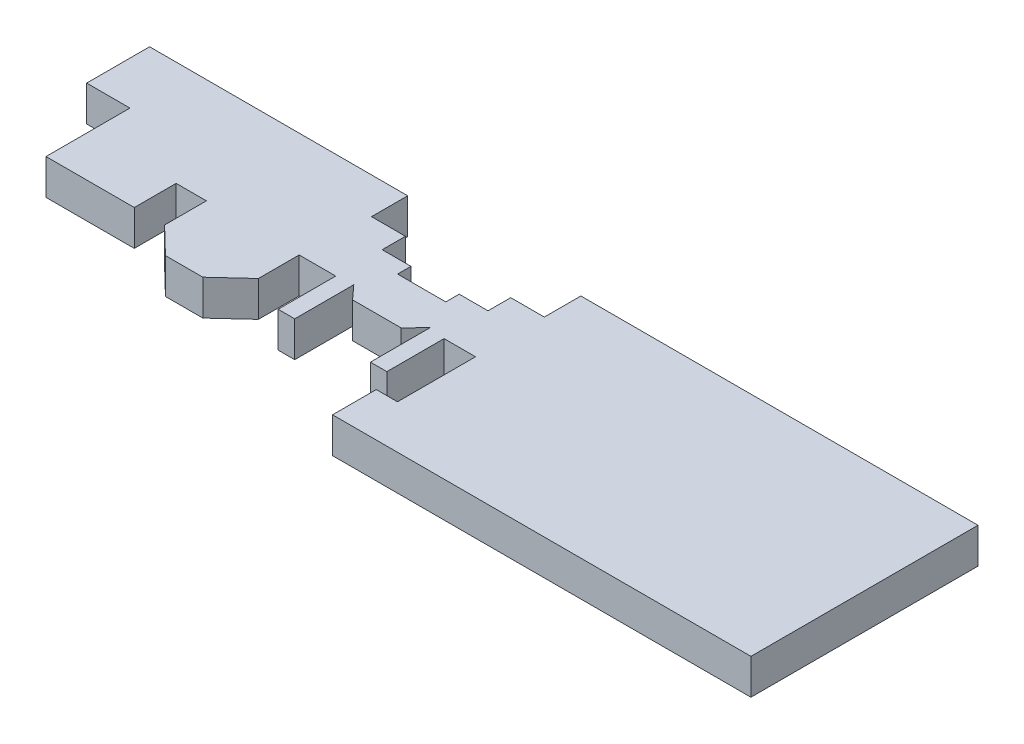
SolidWorks part; units mm, degrees
ref_plane "Front" through (0, 0, 0) normal (0, 0, 1) x (1, 0, 0)
ref_plane "Top" through (0, 0, 0) normal (0, 1, 0) x (1, 0, 0)
ref_plane "Right" through (0, 0, 0) normal (1, 0, 0) x (0, 0, -1)
sketch "Sketch1" plane through (0, 0, 0) normal (0, 1, 0) x (1, 0, 0)
  line L0 (-95852.0448, 1004.5028) -> (-93652.0448, 1004.5028) construction
  line L1 (-92722.4429, 3032.5434) -> (-92722.4429, -4248.038)
  line L2 (-92722.4429, -4248.038) -> (-87714.6303, -4248.038)
  line L3 (-87714.6303, -13961.4489) -> (-77497.684, -13961.4489)
  line L4 (-77497.684, -13961.4489) -> (-77497.684, -9120.8318)
  line L5 (-77497.684, -9120.8318) -> (-73993.9992, -9120.8318)
  line L6 (-73993.9992, -9120.8318) -> (-73993.9992, -13961.4489)
  line L7 (-73993.9992, -13961.4489) -> (-70874.3536, -16978.2439)
  line L8 (-70874.3536, -16978.2439) -> (-66551.4365, -16978.2439)
  line L9 (-66551.4365, -16978.2439) -> (-63204.0372, -13893.8222)
  line L10 (-63204.0372, -13893.8222) -> (-63204.0372, -9177.5359)
  line L11 (-63204.0372, -9177.5359) -> (-58974.2106, -9177.5359)
  line L12 (-58974.2106, -9177.5359) -> (-58974.2106, -15834.789)
  line L13 (-58974.2106, -15834.789) -> (-57060.4997, -15834.789)
  line L14 (-57060.4997, -15834.789) -> (-57060.4997, -8999.6581)
  line L15 (-57060.4997, -8999.6581) -> (-55614.7024, -10587.319)
  line L16 (-55614.7024, -10587.319) -> (-49997.8266, -10587.319)
  line L17 (-49997.8266, -10587.319) -> (-48338.774, -8876.9988)
  line L18 (-48338.774, -8876.9988) -> (-48338.774, -15794.4358)
  line L19 (-48338.774, -15794.4358) -> (-46437.4412, -15794.4358)
  line L20 (-46437.4412, -15794.4358) -> (-46437.4412, -9177.5359)
  line L21 (-46437.4412, -9177.5359) -> (-42795.907, -9177.5359)
  line L22 (-42795.907, -9177.5359) -> (-42795.907, -18201.9351)
  line L23 (-42795.907, -18201.9351) -> (-45253.4333, -18201.9351)
  line L24 (-45253.4333, -18201.9351) -> (-45253.4333, -23262.6588)
  line L25 (-45253.4333, -23262.6588) -> (3158.9575, -23262.6588)
  line L26 (3158.9575, -23262.6588) -> (3158.9575, 3013.36)
  line L27 (3158.9575, 3013.36) -> (-42795.907, 3013.36)
  line L28 (-42795.907, 3013.36) -> (-42795.907, -1217.3234)
  line L29 (-42795.907, -1217.3234) -> (-44543.9492, -1217.3234)
  line L30 (-44543.9492, -1217.3234) -> (-44543.9492, -1414.4498)
  line L31 (-44543.9492, -1414.4498) -> (-42795.907, -1414.4498)
  line L32 (-42795.907, -1414.4498) -> (-42795.907, -5614.4796)
  line L33 (-42795.907, -5614.4796) -> (-15610.0343, -5614.4796)
  line L34 (-15610.0343, -5614.4796) -> (-15610.0343, -1822.8901)
  line L35 (-15610.0343, -1822.8901) -> (-2613.5, -1822.8901)
  line L36 (-2613.5, -1822.8901) -> (-2613.5, 969.6477)
  line L37 (-2613.5, 969.6477) -> (-646.0273, 969.6477)
  line L38 (-646.0273, 969.6477) -> (-646.0273, -9455.9367)
  line L39 (-646.0273, -9455.9367) -> (-2613.5, -9455.9367)
  line L40 (-2613.5, -9455.9367) -> (-2613.5, -5114.7195)
  line L41 (-2613.5, -5114.7195) -> (-12313.0283, -5114.7195)
  line L42 (-12313.0283, -5114.7195) -> (-12313.0283, -11916.6398)
  line L43 (-12313.0283, -11916.6398) -> (3158.9575, -11916.6398)
  line L44 (-62020.0141, -5163.6876) -> (-62020.0141, -5388.889)
  line L45 (-62020.0141, -5388.889) -> (-61911.5095, -5388.889)
  line L46 (-61911.5095, -5388.889) -> (-61911.5095, -5437.5424)
  line L47 (-61911.5095, -5437.5424) -> (-61719.1755, -5437.5424)
  line L48 (-61719.1755, -5437.5424) -> (-61719.1755, -5388.889)
  line L49 (-61719.1755, -5388.889) -> (-61612.0786, -5388.889)
  line L50 (-61612.0786, -5388.889) -> (-61612.0786, -5163.6876)
  line L52 (-61970.0141, -5113.6876) -> (-61662.0786, -5113.6876)
  line L54 (-55960.8823, -4121.4792) -> (-55960.8823, -5665.3674)
  line L55 (-55960.8823, -5665.3674) -> (-49725.6524, -5665.3674)
  line L56 (-49725.6524, -5665.3674) -> (-49725.6524, -4121.4792)
  line L57 (-49725.6524, -4121.4792) -> (-46460.002, -4121.4792)
  line L58 (-46460.002, -4121.4792) -> (-46460.002, 2994.9561)
  line L59 (-47960.002, 4494.9561) -> (-57726.5326, 4494.9561)
  line L60 (-55960.8823, -4121.4792) -> (-59226.5326, -4121.4792)
  line L61 (-59226.5326, -4121.4792) -> (-59226.5326, 2994.9561)
  line L62 (3158.9575, -15328.6011) -> (-37892.4286, -15328.6011)
  line L63 (-37892.4286, -15328.6011) -> (-37892.4286, -18201.9351)
  line L64 (-37892.4286, -18201.9351) -> (-35343.2964, -18201.9351)
  line L65 (-35343.2964, -18201.9351) -> (-35343.2964, -20101.0171)
  line L66 (-35343.2964, -20101.0171) -> (-40314.0738, -20101.0171)
  line L67 (-40314.0738, -20101.0171) -> (-40314.0738, -14936.1956)
  line L68 (-40314.0738, -14936.1956) -> (-42544.3056, -14936.1956)
  line L69 (-42544.3056, -14936.1956) -> (-42544.3056, -13384.4604)
  line L70 (-42544.3056, -13384.4604) -> (-40314.0738, -13384.4604)
  line L71 (-40314.0738, -13384.4604) -> (-40314.0738, -8605.2168)
  line L72 (-50136.471, -10373.3274) -> (-48338.774, -8619.2363)
  line L73 (-48338.774, -8619.2363) -> (-40314.0738, -8605.2168)
  line L76 (-50136.471, -10373.3274) -> (-55355.7793, -10373.3274)
  line L77 (-55355.7793, -10373.3274) -> (-57060.4997, -8626.2285)
  line L78 (-57060.4997, -8626.2285) -> (-63481.1822, -8626.2285)
  line L79 (-63481.1822, -8626.2285) -> (-63481.1822, -13591.9685)
  line L80 (-63481.1822, -13591.9685) -> (-66551.4365, -16662.2229)
  line L81 (-66551.4365, -16662.2229) -> (-70681.0433, -16662.2229)
  line L82 (-70681.0433, -16662.2229) -> (-73704.5204, -13701.7349)
  line L83 (-73704.5204, -13701.7349) -> (-73704.5204, -5657.4342)
  line L84 (-73704.5204, -5657.4342) -> (-69334.0401, -5657.4342)
  line L85 (-69334.0401, -5657.4342) -> (-69334.0401, -2723.9748)
  line L86 (-69334.0401, -2723.9748) -> (-77712.6536, -2723.9748)
  line L87 (-77712.6536, -2723.9748) -> (-77712.6536, -3732.5162)
  line L88 (-87714.6303, -4248.038) -> (-87714.6303, -13961.4489)
  line L89 (-92722.4429, 3032.5434) -> (-62854.9695, 3032.5434)
  line L91 (-62893.6785, -5660.1107) -> (-66861.7243, -5660.1107)
  line L92 (-66861.7243, -5660.1107) -> (-66861.7243, -2698.1933)
  line L93 (-66861.7243, -2698.1933) -> (-65946.0214, -2698.1933)
  line L94 (-65946.0214, -2698.1933) -> (-65946.0214, -1043.5021)
  line L95 (-65946.0214, -1043.5021) -> (-87423.7151, -1043.5021)
  line L96 (-87423.7151, -1043.5021) -> (-87423.7151, -8904.221)
  line L97 (-87423.7151, -8904.221) -> (-84329.7257, -8904.221)
  line L98 (-84329.7257, -8904.221) -> (-84329.7257, -10733.514)
  line L99 (-84329.7257, -10733.514) -> (-82681.1037, -10733.514)
  line L100 (-82681.1037, -10733.514) -> (-82681.1037, -2716.2423)
  line L101 (-82681.1037, -2716.2423) -> (-79338.6918, -2716.2423)
  line L102 (-77712.6536, -3732.5162) -> (-79338.6918, -3732.5162)
  line L103 (-79338.6918, -3732.5162) -> (-79338.6918, -2716.2423)
  line L104 (-62854.9695, 3032.5434) -> (-62854.9695, -1153.6152)
  line L105 (-62854.9695, -1153.6152) -> (-61139.275, -1153.6152)
  line L106 (-61139.275, -1153.6152) -> (-61139.275, -1541.516)
  line L107 (-61139.275, -1541.516) -> (-62893.6785, -1541.516)
  line L108 (-62893.6785, -1541.516) -> (-62893.6785, -5660.1107)
  arc A0 (-62020.0141, -5163.6876) -> (-61970.0141, -5113.6876) centre (-61970.0141, -5163.6876) cw
  arc A1 (-61662.0786, -5113.6876) -> (-61612.0786, -5163.6876) centre (-61662.0786, -5163.6876) cw
  arc A2 (-59226.5326, 2994.9561) -> (-57726.5326, 4494.9561) centre (-57726.5326, 2994.9561) cw
  arc A3 (-46460.002, 2994.9561) -> (-47960.002, 4494.9561) centre (-47960.002, 2994.9561) ccw
  dimension "D1" = 50
  dimension "D2" = 50
  dimension "D3" = 1500
  dimension "D4" = 1500
sketch "Sketch5" plane through (0, 0, 0) normal (0, 1, 0) x (1, 0, 0)
  line L0 (-95852.0448, 1004.5028) -> (-93652.0448, 1004.5028) construction
  line L1 (-92722.4429, 3032.5434) -> (-92722.4429, -4248.038)
  line L2 (-92722.4429, -4248.038) -> (-87714.6303, -4248.038)
  line L3 (-87714.6303, -13961.4489) -> (-77497.684, -13961.4489)
  line L4 (-77497.684, -13961.4489) -> (-77497.684, -9120.8318)
  line L5 (-77497.684, -9120.8318) -> (-73993.9992, -9120.8318)
  line L6 (-73993.9992, -9120.8318) -> (-73993.9992, -13961.4489)
  line L7 (-73993.9992, -13961.4489) -> (-70874.3536, -16978.2439)
  line L8 (-70874.3536, -16978.2439) -> (-66551.4365, -16978.2439)
  line L9 (-66551.4365, -16978.2439) -> (-63204.0372, -13893.8222)
  line L10 (-63204.0372, -13893.8222) -> (-63204.0372, -9177.5359)
  line L11 (-63204.0372, -9177.5359) -> (-58974.2106, -9177.5359)
  line L12 (-58974.2106, -9177.5359) -> (-58974.2106, -15834.789)
  line L13 (-58974.2106, -15834.789) -> (-57060.4997, -15834.789)
  line L14 (-57060.4997, -15834.789) -> (-57060.4997, -8999.6581)
  line L15 (-57060.4997, -8999.6581) -> (-55614.7024, -10587.319)
  line L16 (-55614.7024, -10587.319) -> (-49997.8266, -10587.319)
  line L17 (-49997.8266, -10587.319) -> (-48338.774, -8876.9988)
  line L18 (-48338.774, -8876.9988) -> (-48338.774, -15794.4358)
  line L19 (-48338.774, -15794.4358) -> (-46437.4412, -15794.4358)
  line L20 (-46437.4412, -15794.4358) -> (-46437.4412, -9177.5359)
  line L21 (-46437.4412, -9177.5359) -> (-42795.907, -9177.5359)
  line L22 (-42795.907, -9177.5359) -> (-42795.907, -18201.9351)
  line L23 (-42795.907, -18201.9351) -> (-45253.4333, -18201.9351)
  line L24 (-45253.4333, -18201.9351) -> (-45253.4333, -23262.6588)
  line L25 (-45253.4333, -23262.6588) -> (3158.9575, -23262.6588)
  line L26 (3158.9575, -23262.6588) -> (3158.9575, 3013.36)
  line L27 (3158.9575, 3013.36) -> (-42795.907, 3013.36)
  line L28 (-42795.907, 3013.36) -> (-42795.907, -1217.3234)
  line L29 (-42795.907, -1217.3234) -> (-46681.2907, -1217.3234)
  line L30 (-46460.002, -4121.4792) -> (-46460.002, 2994.9561) construction
  line L31 (-46460.002, -1414.4498) -> (-42795.907, -1414.4498)
  line L32 (-42795.907, -1414.4498) -> (-42795.907, -5614.4796)
  line L33 (-42795.907, -5614.4796) -> (-15610.0343, -5614.4796)
  line L34 (-15610.0343, -5614.4796) -> (-15610.0343, -1822.8901)
  line L35 (-15610.0343, -1822.8901) -> (-2613.5, -1822.8901)
  line L36 (-2613.5, -1822.8901) -> (-2613.5, 969.6477)
  line L37 (-2613.5, 969.6477) -> (-646.0273, 969.6477)
  line L38 (-646.0273, 969.6477) -> (-646.0273, -9455.9367)
  line L39 (-646.0273, -9455.9367) -> (-2613.5, -9455.9367)
  line L40 (-2613.5, -9455.9367) -> (-2613.5, -5114.7195)
  line L41 (-2613.5, -5114.7195) -> (-12313.0283, -5114.7195)
  line L42 (-12313.0283, -5114.7195) -> (-12313.0283, -11916.6398)
  line L43 (-12313.0283, -11916.6398) -> (3158.9575, -11916.6398)
  line L54 (-55960.8823, -4121.4792) -> (-55960.8823, -5665.3674)
  line L55 (-55960.8823, -5665.3674) -> (-49725.6524, -5665.3674)
  line L56 (-49725.6524, -5665.3674) -> (-49725.6524, -4121.4792)
  line L57 (-49725.6524, -4121.4792) -> (-46460.002, -4121.4792)
  line L58 (-46460.002, -4121.4792) -> (-46460.002, -1414.4498)
  line L60 (-55960.8823, -4121.4792) -> (-59226.5326, -4121.4792)
  line L61 (-59226.5326, -4121.4792) -> (-59226.5326, -1541.516)
  line L62 (3158.9575, -15328.6011) -> (-37892.4286, -15328.6011)
  line L63 (-37892.4286, -15328.6011) -> (-37892.4286, -18201.9351)
  line L64 (-37892.4286, -18201.9351) -> (-35343.2964, -18201.9351)
  line L65 (-35343.2964, -18201.9351) -> (-35343.2964, -20101.0171)
  line L66 (-35343.2964, -20101.0171) -> (-40314.0738, -20101.0171)
  line L67 (-40314.0738, -20101.0171) -> (-40314.0738, -14936.1956)
  line L68 (-40314.0738, -14936.1956) -> (-42544.3056, -14936.1956)
  line L69 (-42544.3056, -14936.1956) -> (-42544.3056, -13384.4604)
  line L70 (-42544.3056, -13384.4604) -> (-40314.0738, -13384.4604)
  line L71 (-40314.0738, -13384.4604) -> (-40314.0738, -8605.2168)
  line L72 (-50136.471, -10373.3274) -> (-48338.774, -8619.2363)
  line L73 (-48338.774, -8619.2363) -> (-40314.0738, -8605.2168)
  line L76 (-50136.471, -10373.3274) -> (-55355.7793, -10373.3274)
  line L77 (-55355.7793, -10373.3274) -> (-57060.4997, -8626.2285)
  line L78 (-57060.4997, -8626.2285) -> (-63481.1822, -8626.2285)
  line L79 (-63481.1822, -8626.2285) -> (-63481.1822, -13591.9685)
  line L80 (-63481.1822, -13591.9685) -> (-66551.4365, -16662.2229)
  line L81 (-66551.4365, -16662.2229) -> (-70681.0433, -16662.2229)
  line L82 (-70681.0433, -16662.2229) -> (-73704.5204, -13701.7349)
  line L83 (-73704.5204, -13701.7349) -> (-73704.5204, -5657.4342)
  line L84 (-73704.5204, -5657.4342) -> (-69334.0401, -5657.4342)
  line L85 (-69334.0401, -5657.4342) -> (-69334.0401, -2723.9748)
  line L86 (-69334.0401, -2723.9748) -> (-77712.6536, -2723.9748)
  line L87 (-77712.6536, -2723.9748) -> (-77712.6536, -3732.5162)
  line L88 (-87714.6303, -4248.038) -> (-87714.6303, -13961.4489)
  line L89 (-92722.4429, 3032.5434) -> (-62854.9695, 3032.5434)
  line L91 (-62893.6785, -5660.1107) -> (-66861.7243, -5660.1107)
  line L92 (-66861.7243, -5660.1107) -> (-66861.7243, -2698.1933)
  line L93 (-66861.7243, -2698.1933) -> (-65946.0214, -2698.1933)
  line L94 (-65946.0214, -2698.1933) -> (-65946.0214, -1043.5021)
  line L95 (-65946.0214, -1043.5021) -> (-87423.7151, -1043.5021)
  line L96 (-87423.7151, -1043.5021) -> (-87423.7151, -8904.221)
  line L97 (-87423.7151, -8904.221) -> (-84329.7257, -8904.221)
  line L98 (-84329.7257, -8904.221) -> (-84329.7257, -10733.514)
  line L99 (-84329.7257, -10733.514) -> (-82681.1037, -10733.514)
  line L100 (-82681.1037, -10733.514) -> (-82681.1037, -2716.2423)
  line L101 (-82681.1037, -2716.2423) -> (-79338.6918, -2716.2423)
  line L102 (-77712.6536, -3732.5162) -> (-79338.6918, -3732.5162)
  line L103 (-79338.6918, -3732.5162) -> (-79338.6918, -2716.2423)
  line L104 (-62854.9695, 3032.5434) -> (-62854.9695, -1153.6152)
  line L105 (-62854.9695, -1153.6152) -> (-58927.043, -1153.6152)
  line L107 (-59226.5326, -1541.516) -> (-62893.6785, -1541.516)
  line L108 (-62893.6785, -1541.516) -> (-62893.6785, -5660.1107)
  line L110 (-55593.7762, -5398.4292) -> (-50014.5574, -5398.4292)
  line L111 (-46681.2907, -3848.0726) -> (-46681.2907, -1217.3234)
  line L112 (-55593.7762, -3848.0726) -> (-55593.7762, -5398.4292)
  line L113 (-58927.043, -3848.0726) -> (-58927.043, -1153.6152)
  line L114 (-50014.5574, -5398.4292) -> (-50014.5574, -3848.0726)
  line L115 (-50014.5574, -3848.0726) -> (-46681.2907, -3848.0726)
  line L116 (-55593.7762, -3848.0726) -> (-58927.043, -3848.0726)
extrude "Boss-Extrude1" add sketch "Sketch5" along normal blind 4100
ref_plane "Plane1" through (0, 0, -3022.9517) normal (0, 0, -1) x (-1, 0, 0)
sketch "Sketch8" plane through (0, 0, -3022.9517) normal (0, 0, -1) x (-1, 0, 0)
  line L0 (3231.2525, 3102.6563) -> (7231.2525, 3102.6563)
  line L1 (-2028.4059, 3102.6563) -> (1971.5941, 3102.6563)
  line L2 (-2028.4059, 3102.6563) -> (-2028.4059, 1527.9311)
  line L3 (-2028.4059, 1527.9311) -> (1971.5941, 1527.9311)
  line L4 (1971.5941, 3102.6563) -> (1971.5941, 1527.9311)
  line L9 (3231.2525, 1527.9311) -> (7231.2525, 1527.9311)
  line L10 (7231.2525, 3102.6563) -> (7231.2525, 1527.9311)
  line L11 (3231.2525, 3102.6563) -> (3231.2525, 1527.9311)
  line L12 (17815.6364, 3102.6563) -> (17815.6364, 1527.9311)
  line L13 (8555.978, 3102.6563) -> (12555.978, 3102.6563)
  line L14 (13815.6364, 3102.6563) -> (13815.6364, 1527.9311)
  line L15 (13815.6364, 1527.9311) -> (17815.6364, 1527.9311)
  line L16 (13815.6364, 3102.6563) -> (17815.6364, 3102.6563)
  line L17 (8555.978, 3102.6563) -> (8555.978, 1527.9311)
  line L18 (8555.978, 1527.9311) -> (12555.978, 1527.9311)
  line L19 (12555.978, 3102.6563) -> (12555.978, 1527.9311)
  line L20 (25763.8862, 3102.6563) -> (25763.8862, 1527.9311)
  line L21 (21763.8862, 3102.6563) -> (21763.8862, 1527.9311)
  line L22 (21763.8862, 1527.9311) -> (25763.8862, 1527.9311)
  line L23 (41607.9286, 3102.6563) -> (41607.9286, 1527.9311)
  line L24 (27023.5446, 1527.9311) -> (31023.5446, 1527.9311)
  line L25 (21763.8862, 3102.6563) -> (25763.8862, 3102.6563)
  line L26 (37607.9286, 1527.9311) -> (41607.9286, 1527.9311)
  line L27 (32348.2702, 1527.9311) -> (36348.2702, 1527.9311)
  line L28 (27023.5446, 3102.6563) -> (27023.5446, 1527.9311)
  line L29 (37607.9286, 3102.6563) -> (41607.9286, 3102.6563)
  line L30 (31023.5446, 3102.6563) -> (31023.5446, 1527.9311)
  line L31 (32348.2702, 3102.6563) -> (32348.2702, 1527.9311)
  line L32 (36348.2702, 3102.6563) -> (36348.2702, 1527.9311)
  line L33 (37607.9286, 3102.6563) -> (37607.9286, 1527.9311)
  line L34 (27023.5446, 3102.6563) -> (31023.5446, 3102.6563)
  line L35 (32348.2702, 3102.6563) -> (36348.2702, 3102.6563)
  line L36 (70871.2704, 3102.6563) -> (74871.2704, 3102.6563)
  line L37 (81455.6543, 1527.9311) -> (85455.6543, 1527.9311)
  line L38 (90715.3127, 3102.6563) -> (90715.3127, 1527.9311)
  line L39 (85455.6543, 3102.6563) -> (85455.6543, 1527.9311)
  line L40 (70871.2704, 3102.6563) -> (70871.2704, 1527.9311)
  line L41 (76130.9288, 3102.6563) -> (76130.9288, 1527.9311)
  line L42 (86715.3127, 3102.6563) -> (86715.3127, 1527.9311)
  line L43 (80130.9288, 3102.6563) -> (80130.9288, 1527.9311)
  line L44 (86715.3127, 1527.9311) -> (90715.3127, 1527.9311)
  line L45 (86715.3127, 3102.6563) -> (90715.3127, 3102.6563)
  line L46 (76130.9288, 1527.9311) -> (80130.9288, 1527.9311)
  line L47 (76130.9288, 3102.6563) -> (80130.9288, 3102.6563)
  line L48 (70871.2704, 1527.9311) -> (74871.2704, 1527.9311)
  line L49 (81455.6543, 3102.6563) -> (81455.6543, 1527.9311)
  line L50 (74871.2704, 3102.6563) -> (74871.2704, 1527.9311)
  line L51 (81455.6543, 3102.6563) -> (85455.6543, 3102.6563)
  line L52 (65598.8585, 3102.6563) -> (69598.8585, 3102.6563)
  line L53 (69598.8585, 3102.6563) -> (69598.8585, 1527.9311)
  line L54 (65598.8585, 1527.9311) -> (69598.8585, 1527.9311)
  line L55 (65598.8585, 3102.6563) -> (65598.8585, 1527.9311)
sketch "Sketch10" plane through (0, 0, -3022.9517) normal (0, 0, -1) x (-1, 0, 0)
  line L0 (3231.2525, 3102.6563) -> (7231.2525, 3102.6563)
  line L1 (-2028.4059, 3102.6563) -> (1971.5941, 3102.6563)
  line L2 (-2028.4059, 3102.6563) -> (-2028.4059, 1527.9311)
  line L3 (-2028.4059, 1527.9311) -> (1971.5941, 1527.9311)
  line L4 (1971.5941, 3102.6563) -> (1971.5941, 1527.9311)
  line L9 (3231.2525, 1527.9311) -> (7231.2525, 1527.9311)
  line L10 (7231.2525, 3102.6563) -> (7231.2525, 1527.9311)
  line L11 (3231.2525, 3102.6563) -> (3231.2525, 1527.9311)
  line L12 (17815.6364, 3102.6563) -> (17815.6364, 1527.9311)
  line L13 (8555.978, 3102.6563) -> (12555.978, 3102.6563)
  line L14 (13815.6364, 3102.6563) -> (13815.6364, 1527.9311)
  line L15 (13815.6364, 1527.9311) -> (17815.6364, 1527.9311)
  line L16 (13815.6364, 3102.6563) -> (17815.6364, 3102.6563)
  line L17 (8555.978, 3102.6563) -> (8555.978, 1527.9311)
  line L18 (8555.978, 1527.9311) -> (12555.978, 1527.9311)
  line L19 (12555.978, 3102.6563) -> (12555.978, 1527.9311)
  line L20 (25763.8862, 3102.6563) -> (25763.8862, 1527.9311)
  line L21 (21763.8862, 3102.6563) -> (21763.8862, 1527.9311)
  line L22 (21763.8862, 1527.9311) -> (25763.8862, 1527.9311)
  line L23 (41607.9286, 3102.6563) -> (41607.9286, 1527.9311)
  line L24 (27023.5446, 1527.9311) -> (31023.5446, 1527.9311)
  line L25 (21763.8862, 3102.6563) -> (25763.8862, 3102.6563)
  line L26 (37607.9286, 1527.9311) -> (41607.9286, 1527.9311)
  line L27 (32348.2702, 1527.9311) -> (36348.2702, 1527.9311)
  line L28 (27023.5446, 3102.6563) -> (27023.5446, 1527.9311)
  line L29 (37607.9286, 3102.6563) -> (41607.9286, 3102.6563)
  line L30 (31023.5446, 3102.6563) -> (31023.5446, 1527.9311)
  line L31 (32348.2702, 3102.6563) -> (32348.2702, 1527.9311)
  line L32 (36348.2702, 3102.6563) -> (36348.2702, 1527.9311)
  line L33 (37607.9286, 3102.6563) -> (37607.9286, 1527.9311)
  line L34 (27023.5446, 3102.6563) -> (31023.5446, 3102.6563)
  line L35 (32348.2702, 3102.6563) -> (36348.2702, 3102.6563)
  line L36 (70871.2704, 3102.6563) -> (74871.2704, 3102.6563)
  line L37 (81455.6543, 1527.9311) -> (85455.6543, 1527.9311)
  line L38 (90715.3127, 3102.6563) -> (90715.3127, 1527.9311)
  line L39 (85455.6543, 3102.6563) -> (85455.6543, 1527.9311)
  line L40 (70871.2704, 3102.6563) -> (70871.2704, 1527.9311)
  line L41 (76130.9288, 3102.6563) -> (76130.9288, 1527.9311)
  line L42 (86715.3127, 3102.6563) -> (86715.3127, 1527.9311)
  line L43 (80130.9288, 3102.6563) -> (80130.9288, 1527.9311)
  line L44 (86715.3127, 1527.9311) -> (90715.3127, 1527.9311)
  line L45 (86715.3127, 3102.6563) -> (90715.3127, 3102.6563)
  line L46 (76130.9288, 1527.9311) -> (80130.9288, 1527.9311)
  line L47 (76130.9288, 3102.6563) -> (80130.9288, 3102.6563)
  line L48 (70871.2704, 1527.9311) -> (74871.2704, 1527.9311)
  line L49 (81455.6543, 3102.6563) -> (81455.6543, 1527.9311)
  line L50 (74871.2704, 3102.6563) -> (74871.2704, 1527.9311)
  line L51 (81455.6543, 3102.6563) -> (85455.6543, 3102.6563)
  line L52 (65598.8585, 3102.6563) -> (69598.8585, 3102.6563)
  line L53 (69598.8585, 3102.6563) -> (69598.8585, 1527.9311)
  line L54 (65598.8585, 1527.9311) -> (69598.8585, 1527.9311)
  line L55 (65598.8585, 3102.6563) -> (65598.8585, 1527.9311)
extrude "Cut-Extrude2" cut sketch "Sketch8" against normal blind 1000 and the other way blind 360
ref_plane "Plane2" through (0, 4100, 0) normal (0, 1, 0) x (1, 0, 0)
sketch "Sketch11" plane through (0, 4100, 0) normal (0, 1, 0) x (1, 0, 0)
  line L0 (-95852.0448, 1004.5028) -> (-93652.0448, 1004.5028) construction
  line L1 (-92722.4429, 3032.5434) -> (-92722.4429, -4248.038)
  line L2 (-92722.4429, -4248.038) -> (-87714.6303, -4248.038)
  line L3 (-87714.6303, -13961.4489) -> (-77497.684, -13961.4489)
  line L4 (-77497.684, -13961.4489) -> (-77497.684, -9120.8318)
  line L5 (-77497.684, -9120.8318) -> (-73993.9992, -9120.8318)
  line L6 (-73993.9992, -9120.8318) -> (-73993.9992, -13961.4489)
  line L7 (-73993.9992, -13961.4489) -> (-70874.3536, -16978.2439)
  line L8 (-70874.3536, -16978.2439) -> (-66551.4365, -16978.2439)
  line L9 (-66551.4365, -16978.2439) -> (-63204.0372, -13893.8222)
  line L10 (-63204.0372, -13893.8222) -> (-63204.0372, -9177.5359)
  line L11 (-63204.0372, -9177.5359) -> (-58974.2106, -9177.5359)
  line L12 (-58974.2106, -9177.5359) -> (-58974.2106, -15834.789)
  line L13 (-58974.2106, -15834.789) -> (-57060.4997, -15834.789)
  line L14 (-57060.4997, -15834.789) -> (-57060.4997, -8999.6581)
  line L15 (-57060.4997, -8999.6581) -> (-55614.7024, -10587.319)
  line L16 (-55614.7024, -10587.319) -> (-49997.8266, -10587.319)
  line L17 (-49997.8266, -10587.319) -> (-48338.774, -8876.9988)
  line L18 (-48338.774, -8876.9988) -> (-48338.774, -15794.4358)
  line L19 (-48338.774, -15794.4358) -> (-46437.4412, -15794.4358)
  line L20 (-46437.4412, -15794.4358) -> (-46437.4412, -9177.5359)
  line L21 (-46437.4412, -9177.5359) -> (-42795.907, -9177.5359)
  line L22 (-42795.907, -9177.5359) -> (-42795.907, -18201.9351)
  line L23 (-42795.907, -18201.9351) -> (-45253.4333, -18201.9351)
  line L24 (-45253.4333, -18201.9351) -> (-45253.4333, -23262.6588)
  line L25 (-45253.4333, -23262.6588) -> (3158.9575, -23262.6588)
  line L26 (3158.9575, -23262.6588) -> (3158.9575, 3013.36)
  line L27 (3158.9575, 3013.36) -> (-42795.907, 3013.36)
  line L28 (-42795.907, 3013.36) -> (-42795.907, -1217.3234)
  line L29 (-42795.907, -1217.3234) -> (-44543.9492, -1217.3234)
  line L30 (-44543.9492, -1217.3234) -> (-44543.9492, -1414.4498)
  line L31 (-44543.9492, -1414.4498) -> (-42795.907, -1414.4498)
  line L32 (-42795.907, -1414.4498) -> (-42795.907, -5614.4796)
  line L33 (-42795.907, -5614.4796) -> (-15610.0343, -5614.4796)
  line L34 (-15610.0343, -5614.4796) -> (-15610.0343, -1822.8901)
  line L35 (-15610.0343, -1822.8901) -> (-2613.5, -1822.8901)
  line L36 (-2613.5, -1822.8901) -> (-2613.5, 969.6477)
  line L37 (-2613.5, 969.6477) -> (-646.0273, 969.6477)
  line L38 (-646.0273, 969.6477) -> (-646.0273, -9455.9367)
  line L39 (-646.0273, -9455.9367) -> (-2613.5, -9455.9367)
  line L40 (-2613.5, -9455.9367) -> (-2613.5, -5114.7195)
  line L41 (-2613.5, -5114.7195) -> (-12313.0283, -5114.7195)
  line L42 (-12313.0283, -5114.7195) -> (-12313.0283, -11916.6398)
  line L43 (-12313.0283, -11916.6398) -> (3158.9575, -11916.6398)
  line L44 (-62020.0141, -5163.6876) -> (-62020.0141, -5388.889)
  line L45 (-62020.0141, -5388.889) -> (-61911.5095, -5388.889)
  line L46 (-61911.5095, -5388.889) -> (-61911.5095, -5437.5424)
  line L47 (-61911.5095, -5437.5424) -> (-61719.1755, -5437.5424)
  line L48 (-61719.1755, -5437.5424) -> (-61719.1755, -5388.889)
  line L49 (-61719.1755, -5388.889) -> (-61612.0786, -5388.889)
  line L50 (-61612.0786, -5388.889) -> (-61612.0786, -5163.6876)
  line L52 (-61970.0141, -5113.6876) -> (-61662.0786, -5113.6876)
  line L54 (-55960.8823, -4121.4792) -> (-55960.8823, -5665.3674)
  line L55 (-55960.8823, -5665.3674) -> (-49725.6524, -5665.3674)
  line L56 (-49725.6524, -5665.3674) -> (-49725.6524, -4121.4792)
  line L57 (-49725.6524, -4121.4792) -> (-46460.002, -4121.4792)
  line L58 (-46460.002, -4121.4792) -> (-46460.002, -1217.3234)
  line L60 (-55960.8823, -4121.4792) -> (-59226.5326, -4121.4792)
  line L61 (-59226.5326, -4121.4792) -> (-59226.5326, -1153.6152)
  line L62 (3158.9575, -15328.6011) -> (-37892.4286, -15328.6011)
  line L63 (-37892.4286, -15328.6011) -> (-37892.4286, -18201.9351)
  line L64 (-37892.4286, -18201.9351) -> (-35343.2964, -18201.9351)
  line L65 (-35343.2964, -18201.9351) -> (-35343.2964, -20101.0171)
  line L66 (-35343.2964, -20101.0171) -> (-40314.0738, -20101.0171)
  line L67 (-40314.0738, -20101.0171) -> (-40314.0738, -14936.1956)
  line L68 (-40314.0738, -14936.1956) -> (-42544.3056, -14936.1956)
  line L69 (-42544.3056, -14936.1956) -> (-42544.3056, -13384.4604)
  line L70 (-42544.3056, -13384.4604) -> (-40314.0738, -13384.4604)
  line L71 (-40314.0738, -13384.4604) -> (-40314.0738, -8605.2168)
  line L72 (-50136.471, -10373.3274) -> (-48338.774, -8619.2363)
  line L73 (-48338.774, -8619.2363) -> (-40314.0738, -8605.2168)
  line L76 (-50136.471, -10373.3274) -> (-55355.7793, -10373.3274)
  line L77 (-55355.7793, -10373.3274) -> (-57060.4997, -8626.2285)
  line L78 (-57060.4997, -8626.2285) -> (-63481.1822, -8626.2285)
  line L79 (-63481.1822, -8626.2285) -> (-63481.1822, -13591.9685)
  line L80 (-63481.1822, -13591.9685) -> (-66551.4365, -16662.2229)
  line L81 (-66551.4365, -16662.2229) -> (-70681.0433, -16662.2229)
  line L82 (-70681.0433, -16662.2229) -> (-73704.5204, -13701.7349)
  line L83 (-73704.5204, -13701.7349) -> (-73704.5204, -5657.4342)
  line L84 (-73704.5204, -5657.4342) -> (-69334.0401, -5657.4342)
  line L85 (-69334.0401, -5657.4342) -> (-69334.0401, -2723.9748)
  line L86 (-69334.0401, -2723.9748) -> (-77712.6536, -2723.9748)
  line L87 (-77712.6536, -2723.9748) -> (-77712.6536, -3732.5162)
  line L88 (-87714.6303, -4248.038) -> (-87714.6303, -13961.4489)
  line L89 (-92722.4429, 3032.5434) -> (-62854.9695, 3032.5434)
  line L91 (-62893.6785, -5660.1107) -> (-66861.7243, -5660.1107)
  line L92 (-66861.7243, -5660.1107) -> (-66861.7243, -2698.1933)
  line L93 (-66861.7243, -2698.1933) -> (-65946.0214, -2698.1933)
  line L94 (-65946.0214, -2698.1933) -> (-65946.0214, -1043.5021)
  line L95 (-65946.0214, -1043.5021) -> (-87423.7151, -1043.5021)
  line L96 (-87423.7151, -1043.5021) -> (-87423.7151, -8904.221)
  line L97 (-87423.7151, -8904.221) -> (-84329.7257, -8904.221)
  line L98 (-84329.7257, -8904.221) -> (-84329.7257, -10733.514)
  line L99 (-84329.7257, -10733.514) -> (-82681.1037, -10733.514)
  line L100 (-82681.1037, -10733.514) -> (-82681.1037, -2716.2423)
  line L101 (-82681.1037, -2716.2423) -> (-79338.6918, -2716.2423)
  line L102 (-77712.6536, -3732.5162) -> (-79338.6918, -3732.5162)
  line L103 (-79338.6918, -3732.5162) -> (-79338.6918, -2716.2423)
  line L104 (-62854.9695, 3032.5434) -> (-62854.9695, -1153.6152)
  line L105 (-62854.9695, -1153.6152) -> (-61139.275, -1153.6152)
  line L106 (-61139.275, -1153.6152) -> (-61139.275, -1541.516)
  line L107 (-61139.275, -1541.516) -> (-62893.6785, -1541.516)
  line L108 (-62893.6785, -1541.516) -> (-62893.6785, -5660.1107)
  line L109 (-61139.275, -1153.6152) -> (-59226.5326, -1153.6152)
  line L110 (-44543.9492, -1217.3234) -> (-46460.002, -1217.3234)
  line L111 (-55593.7762, -3848.0726) -> (-55593.7762, -5398.4292)
  arc A0 (-62020.0141, -5163.6876) -> (-61970.0141, -5113.6876) centre (-61970.0141, -5163.6876) cw
  arc A1 (-61662.0786, -5113.6876) -> (-61612.0786, -5163.6876) centre (-61662.0786, -5163.6876) cw
  dimension "D1" = 50
  dimension "D2" = 50
extrude "Boss-Extrude2" add sketch "Sketch11" against normal blind 400 contours L108 L107 L106 L105 L104 L89 L1 L2 L88 L3 L4 L5 L6 L7 L8 L9 L10 L11 L12 L13 L14 L15 L16 L17 L18 L19 L20 L21 L22 L23 L24 L25 L26 L62 L63 L64 L65 L66 L67 L68 L69 L70 L71 L73 L72 L76 L77 L78 L79 L80 L81 | L30 L110 L58 L57 L56 L55 L54 L60 L61 L109 L106 L107 L108 L91 L92 L93 L94 L95 L96 L97 L98 L99 L100 L101 L103 L102 L87 L86 L85 L84 L83 L82 L81 L80 L79 L78 L77 L76 L72 L73 L71 L70 L69 L68 L67 L66 L65 L64 L63 L62 L26 | L42 L43 L26 L27 L28 L29 L30 L31 L32 L33 L34 L35 L36 L37 L38 L39 L40 L41
extrude "Boss-Extrude3" add sketch "Sketch10" against normal blind 150
